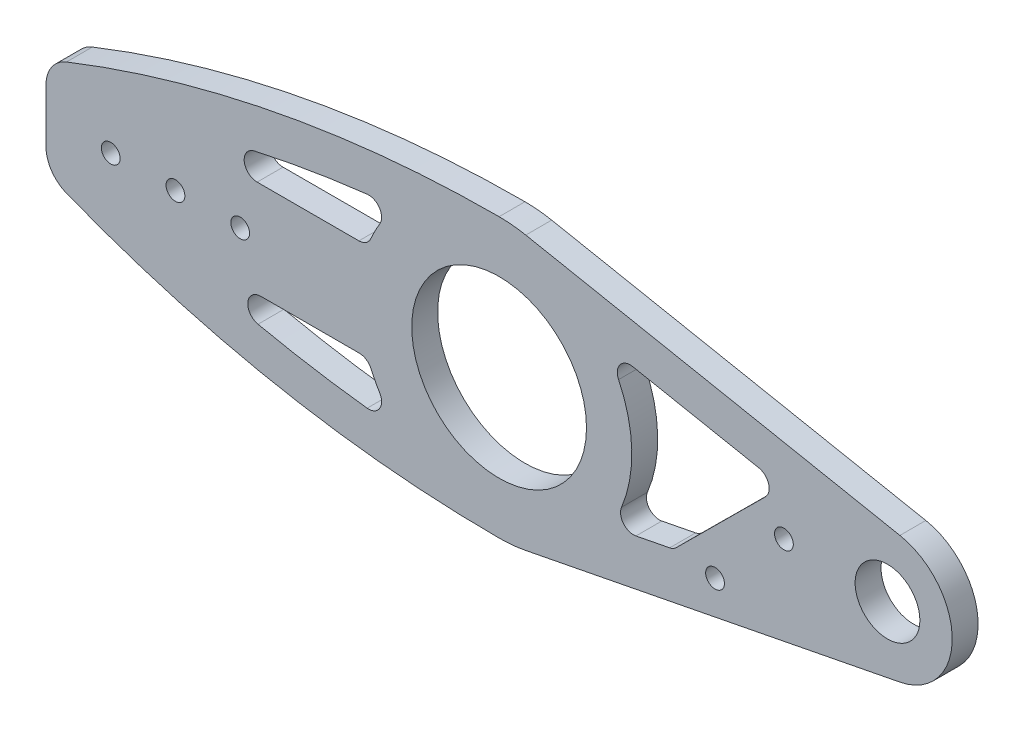
SolidWorks part; units mm, degrees
material "Thornel Mat VMA"
ref_plane "前视基准面" through (0, 0, 0) normal (0, 0, 1) x (1, 0, 0)
ref_plane "上视基准面" through (0, 0, 0) normal (0, 1, 0) x (1, 0, 0)
ref_plane "右视基准面" through (0, 0, 0) normal (1, 0, 0) x (0, 0, -1)
other "Configuration Table"
sketch "草图1" plane through (0, 0, 0) normal (0, 0, 1) x (1, 0, 0)
  line L0 (0, -7.5) -> (15, -7.5) construction
  line L1 (0, 0) -> (-55, 0) construction
  line L2 (0, 0) -> (0, -15) construction
  line L3 (0, -15) -> (-55, -15) construction
  line L4 (-55, 0) -> (-55, -15) construction
  line L5 (-5.1494, 0) -> (-55, 0) construction
  line L6 (-55, 0) -> (-55, -15)
  line L7 (-55, -15) -> (-5.1494, -15) construction
  line L8 (19.1208, 13.6014) -> (76.9167, 2.3146)
  line L9 (19.1208, -28.6014) -> (76.9167, -17.3146)
  circle A0 centre (15, -7.5) radius 13.5
  arc A1 (-5.1494, -15) -> (19.1208, -28.6014) centre (15, -7.5) ccw construction
  circle A2 centre (75, -7.5) radius 5
  arc A3 (76.9167, -17.3146) -> (76.9167, 2.3146) centre (75, -7.5) ccw
  arc A4 (19.1208, 13.6014) -> (-5.1494, 0) centre (15, -7.5) ccw construction
  arc A5 (-55, -15) -> (15, -29) centre (15, 153) ccw
  arc A6 (-55, 0) -> (15, 14) centre (15, -168) cw
  arc A7 (15, 14) -> (19.1208, 13.6014) centre (15, -7.5) cw
  arc A8 (15, -29) -> (19.1208, -28.6014) centre (15, -7.5) ccw
  dimension "D2" = 27
  dimension "D4" = 8
  dimension "D6" = 10
  dimension "D8" = 5
  dimension "D1" = 15
  dimension "D3" = 15
  dimension "D5" = 55
  dimension "D7" = 60
extrude "凸台-拉伸1" add sketch "草图1" along normal blind 4
sketch "草图2" plane through (0, 0, 4) normal (0, 0, 1) x (1, 0, 0)
  line L0 (-55, -7.5) -> (1.5, -7.5) construction
  line L1 (-55, 0) -> (-55, -15) construction
  line L2 (-45, -7.5) -> (-35, -7.5) construction
  circle A0 centre (15, -7.5) radius 13.5 construction
  circle A1 centre (-45, -7.5) radius 1.45
  circle A2 centre (-35, -7.5) radius 1.45
  circle A3 centre (-25, -7.5) radius 1.45
  dimension "D1" = 2.9
  dimension "D2" = 10
  dimension "D4" = 10
  dimension "D3" = 3
extrude "切除-拉伸1" cut sketch "草图2" against normal through all
sketch "草图4" plane through (0, 0, 0) normal (0, 0, -1) x (-1, 0, 0)
  line L0 (-59, -7.1173) -> (-48.3599, -17.6903) construction
  circle A0 centre (-59, -7.1173) radius 1.45
  circle A1 centre (-48.3599, -17.6903) radius 1.45
  circle A2 centre (-59, -7.1173) radius 2.75 construction
  circle A3 centre (-48.3599, -17.6903) radius 2.75 construction
  circle A4 centre (-75, -7.5) radius 5 construction
  arc A5 (-66.9253, -1.6009) -> (-19.8421, -38.2211) centre (20.5776, 62.325) ccw construction
  point P2 (-75, -7.5)
  dimension "D2" = 2.9
  dimension "D6" = 5.5
  dimension "D7" = 5.5
  dimension "D3" = 15
  dimension "D5" = 16
extrude "切除-拉伸3" cut sketch "草图4" against normal through all
fillet "圆角4" radius 5 2 edges at (-55, -15, 2) (-55, 0, 2)
sketch "草图5" plane through (0, 0, 4) normal (0, 0, 1) x (1, 0, 0)
  line L0 (-55, -3.3671) -> (-55, -11.6329) construction
  line L1 (-37.6627, -0.0636) -> (-5.3094, -0.0636)
  line L3 (-37.2718, -15.0585) -> (-5.2643, -15.0585)
  line L4 (59, -7.1173) -> (48.3599, -17.6903) construction
  line L5 (31.1385, 5.1412) -> (58.8054, -0.2618)
  line L6 (58.8054, -0.2618) -> (41.9501, -17.0109)
  line L7 (76.9167, 2.3146) -> (19.1208, 13.6014) construction
  line L8 (32.0019, -18.9537) -> (41.9501, -17.0109)
  line L9 (19.1208, -28.6014) -> (76.9167, -17.3146) construction
  arc A0 (31.1385, 5.1412) -> (32.0019, -18.9537) centre (15, -7.5) cw
  arc A1 (-5.2643, -15.0585) -> (-0.7795, -22.2912) centre (15, -7.5) ccw
  circle A2 centre (15, -7.5) radius 13.5 construction
  arc A8 (15, 8) -> (-49.6328, -4.2972) centre (15, -168) ccw
  arc A9 (-0.7795, 7.2912) -> (-37.6627, -0.0636) centre (15, -168) ccw
  arc A10 (-0.7795, 7.2912) -> (-5.3094, -0.0636) centre (15, -7.5) ccw
  arc A11 (-49.6328, -10.7028) -> (15, -23) centre (15, 153) ccw
  arc A12 (-37.2718, -15.0585) -> (-0.7795, -22.2912) centre (15, 153) ccw
  point P10 (-5.3094, -7.5)
  dimension "D6" = 7
  dimension "D3" = 15
  dimension "D4" = 32.3533
  dimension "D5" = 17.3373
  dimension "D7" = 6
  dimension "D8" = 5
  dimension "D9" = 7
  dimension "D1" = 6
  dimension "D2" = 6
extrude "切除-拉伸4" cut sketch "草图5" against normal through all
fillet "圆角5" radius 2 10 edges at (-5.3094, -0.0636, 2) (-5.2643, -15.0585, 2) (-0.7795, -22.2912, 2) (-37.2718, -15.0585, 2) (-0.7795, 7.2912, 2) (-37.6627, -0.0636, 2) (58.8054, -0.2618, 2) (41.9501, -17.0109, 2) (31.1385, 5.1412, 2) (32.0019, -18.9537, 2)
